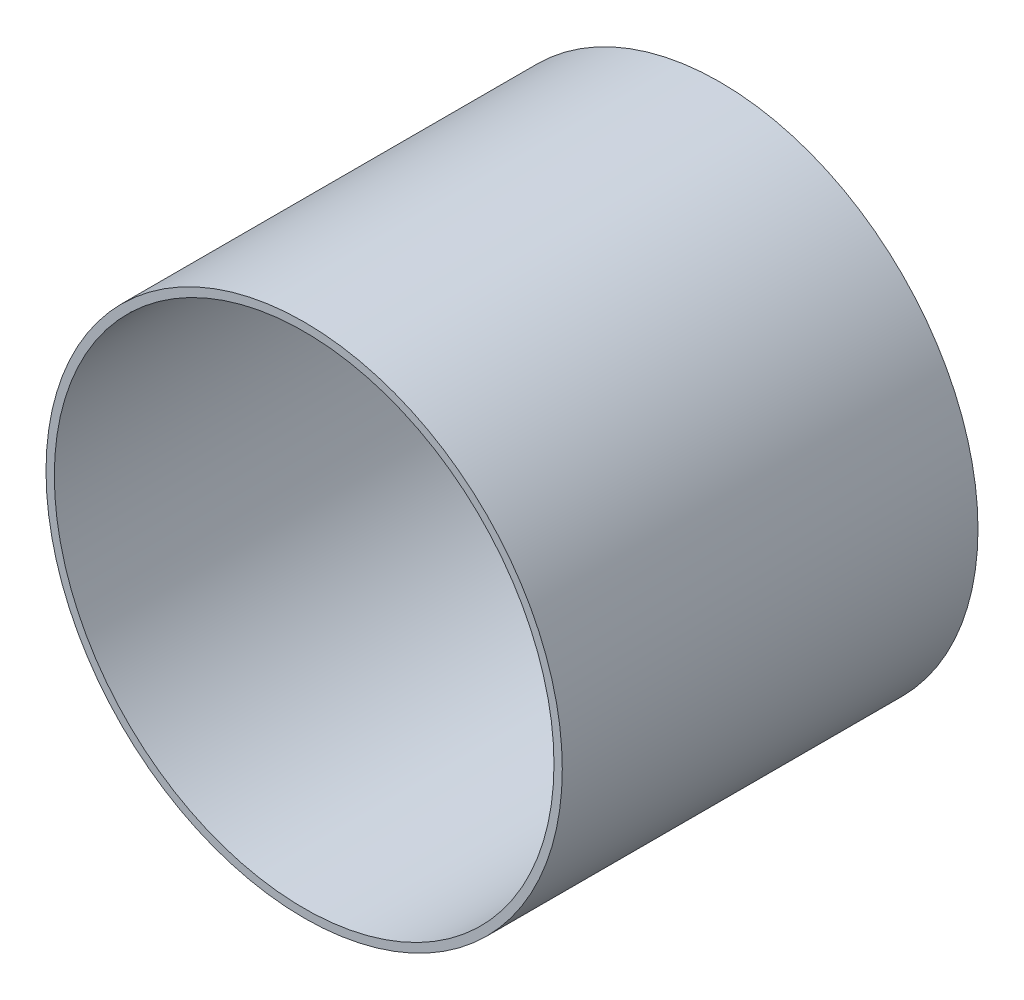
SolidWorks part; units mm, degrees
material "Латунь"
ref_plane "Спереди" through (0, 0, 0) normal (0, 0, 1) x (1, 0, 0)
ref_plane "Сверху" through (0, 0, 0) normal (0, 1, 0) x (1, 0, 0)
ref_plane "Справа" through (0, 0, 0) normal (1, 0, 0) x (0, 0, -1)
other "Configuration Table"
sketch "Эскиз1" plane through (0, 0, 0) normal (0, 0, 1) x (1, 0, 0)
  circle A0 centre (0, 0) radius 30.05
  circle A1 centre (0, 0) radius 31.05
  dimension "D1" = 60.1
  dimension "D2" = 1
extrude "Бобышка-Вытянуть1" add sketch "Эскиз1" along normal blind 50
